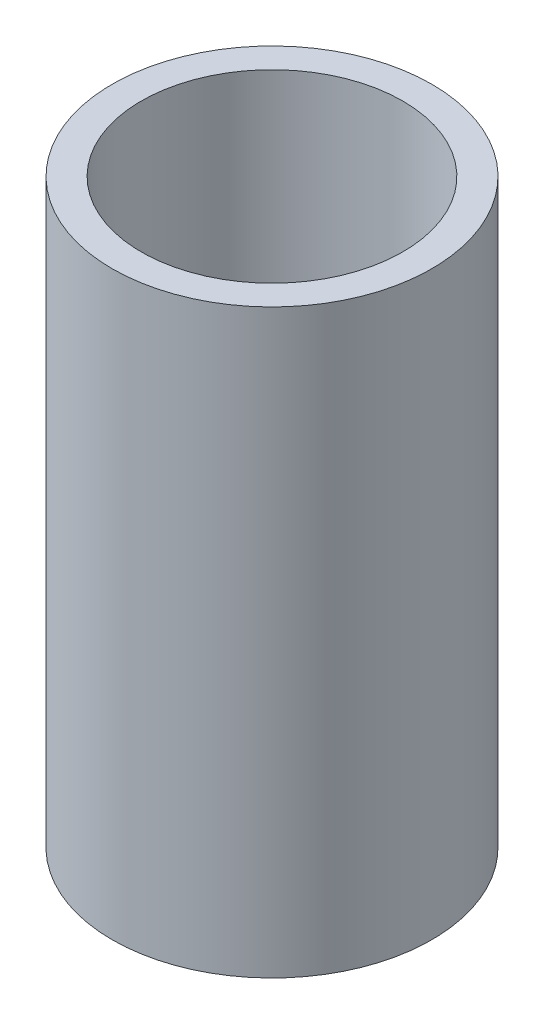
SolidWorks part; units mm, degrees
ref_plane "Спереди" through (0, 0, 0) normal (0, 0, 1) x (1, 0, 0)
ref_plane "Сверху" through (0, 0, 0) normal (0, 1, 0) x (1, 0, 0)
ref_plane "Справа" through (0, 0, 0) normal (1, 0, 0) x (0, 0, -1)
sketch "Эскиз1" plane through (0, 0, 0) normal (0, 0, 1) x (1, 0, 0)
  line L0 (0, -110.6031) -> (0, 130.0787) construction
  line L1 (45, 100) -> (55, 100)
  line L2 (45, 100) -> (45, -100)
  line L3 (45, -100) -> (55, -100)
  line L4 (55, 100) -> (55, -100)
  point P4 (45, 0)
  dimension "D1" = 10
  dimension "D2" = 200
  dimension "D3" = 45
revolve "Повернуть1" add sketch "Эскиз1" angle 360 about L0
surface "Поверхность-Промежуточная поверхность1" parameters "D0"=10000
